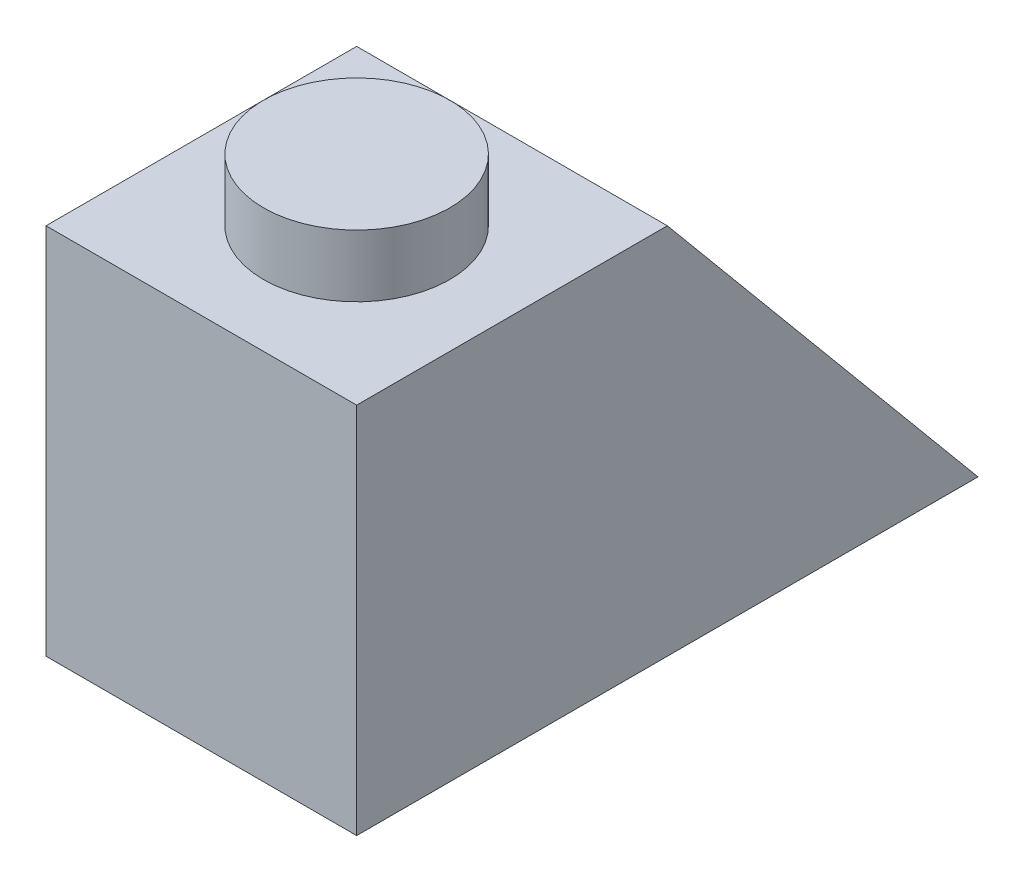
SolidWorks part; units mm, degrees
ref_plane "Front Plane" through (0, 0, 0) normal (0, 0, 1) x (1, 0, 0)
ref_plane "Top Plane" through (0, 0, 0) normal (0, 1, 0) x (1, 0, 0)
ref_plane "Right Plane" through (0, 0, 0) normal (1, 0, 0) x (0, 0, -1)
sketch "Sketch1" plane through (0, 0, 0) normal (1, 0, 0) x (0, 0, -1)
  line L0 (0, 0) -> (16, 0)
  line L1 (16, 0) -> (8, 9.6)
  line L2 (8, 9.6) -> (0, 9.6)
  line L3 (0, 9.6) -> (0, 0)
  dimension "D1" = 9.6
  dimension "D2" = 8
  dimension "D3" = 16
extrude "Boss-Extrude1" add sketch "Sketch1" along normal blind 8
sketch "Sketch2" plane through (0, 9.6, 0) normal (0, 1, 0) x (1, 0, 0)
  line L0 (0, 4) -> (4, 4) construction
  line L1 (0, 8) -> (0, 0) construction
  circle A0 centre (4, 4) radius 2.4
  dimension "D2" = 4.8
  dimension "D1" = 4
extrude "Boss-Extrude2" add sketch "Sketch2" along normal blind 1.6
shell "Shell1" thickness 1.6
